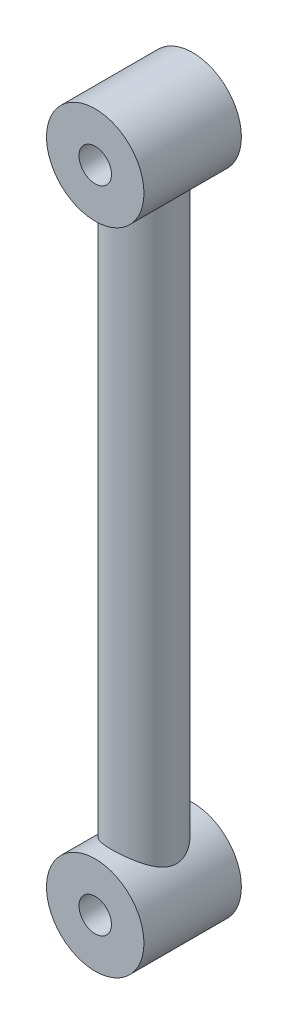
SolidWorks part; units mm, degrees
ref_plane "Front" through (0, 0, 0) normal (0, 0, 1) x (1, 0, 0)
ref_plane "Top" through (0, 0, 0) normal (0, 1, 0) x (1, 0, 0)
ref_plane "Right" through (0, 0, 0) normal (1, 0, 0) x (0, 0, -1)
sketch "草图1" plane through (0, 0, 0) normal (0, 0, 1) x (1, 0, 0)
  circle A0 centre (0, 0) radius 0.5
  circle A1 centre (0, 0) radius 1.5
extrude "凸台-拉伸1" add sketch "草图1" along normal blind 3
ref_plane "基准面1" through (0, 10, 0) normal (0, 1, 0) x (1, 0, 0)
sketch "草图2" plane through (0, 10, 0) normal (0, 1, 0) x (1, 0, 0)
  line L0 (0, 7.4859) -> (0, -9.6645) construction
  line L1 (3.83, 0) -> (-6.5537, 0) construction
  circle A0 centre (0, -1.5) radius 1
  dimension "D1" = 1.5
extrude "凸台-拉伸2" add sketch "草图2" against normal up to surface (8.5 mm away)
mirror "镜向1" about plane through (0, 10, 0) normal (0, 1, 0) of "凸台-拉伸1", "凸台-拉伸2"
mirror "镜向2" about plane through (0, 10, 0) normal (0, 1, 0) of "凸台-拉伸1"
